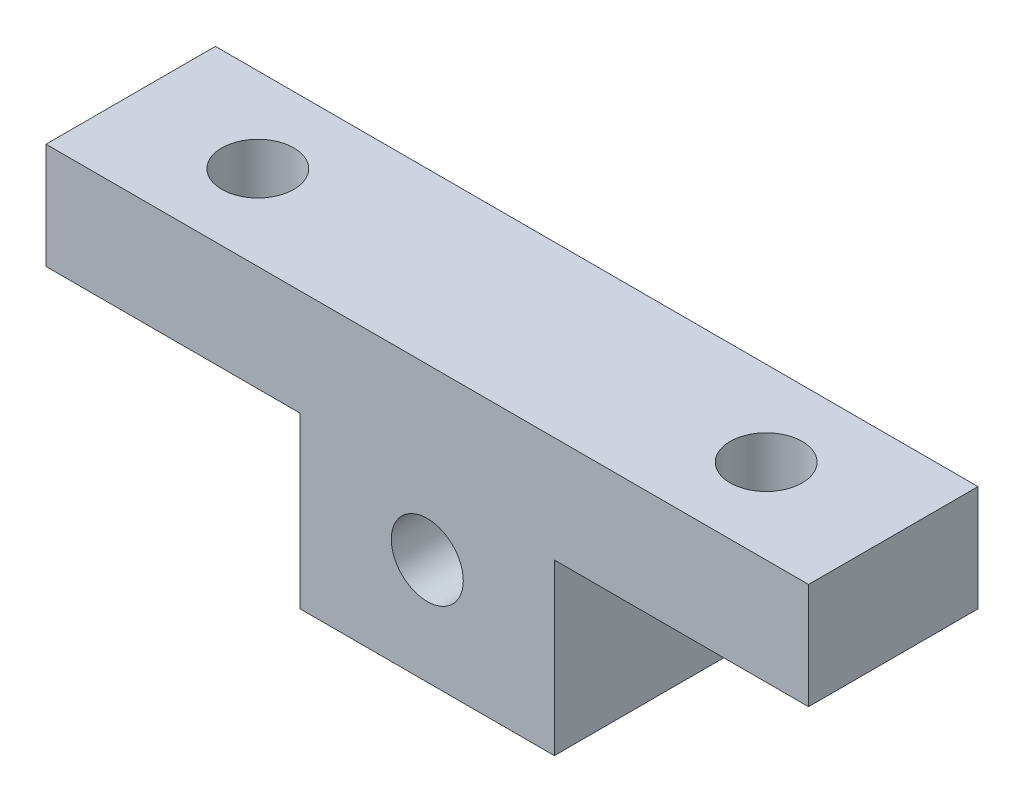
SolidWorks part; units mm, degrees
ref_plane "Front Plane" through (0, 0, 0) normal (0, 0, 1) x (1, 0, 0)
ref_plane "Top Plane" through (0, 0, 0) normal (0, 1, 0) x (1, 0, 0)
ref_plane "Right Plane" through (0, 0, 0) normal (1, 0, 0) x (0, 0, -1)
sketch "Sketch1" plane through (0, 0, 0) normal (0, 0, 1) x (1, 0, 0)
  line L0 (0, 0) -> (0, 5)
  line L1 (0, 5) -> (36, 5)
  line L2 (36, 5) -> (36, 0)
  line L3 (36, 0) -> (24, 0)
  line L4 (24, 0) -> (24, -8)
  line L5 (24, -8) -> (12, -8)
  line L6 (12, -8) -> (12, 0)
  line L7 (12, 0) -> (0, 0)
  dimension "D1" = 36
  dimension "D2" = 12
  dimension "D3" = 12
  dimension "D4" = 12
  dimension "D5" = 5
  dimension "D6" = 8
extrude "Boss-Extrude1" add sketch "Sketch1" along normal blind 8
hole_wizard "M3 Clearance Hole1" positions "Sketch2" profile "Sketch3" hole size "M3" standard "ANSI Metric" end condition through all
sketch "Sketch2" plane through (0, 0, 8) normal (0, 0, 1) x (1, 0, 0)
  line L1 (12, 0) -> (12, -8) construction
  line L2 (36, 5) -> (0, 5) construction
  point P0 (18, -3)
  dimension "D1" = 8
  dimension "D2" = 6
sketch "Sketch3" plane through (18, -3, 8) normal (1, 0, 0) x (0, -1, 0)
  line L0 (0, 0) -> (0, 8)
  line L1 (0, 8) -> (1.7, 8)
  line L2 (1.7, 8) -> (1.7, 0)
  line L5 (1.7, 0) -> (0, 0)
  line L11 (0, -6.35) -> (0, 107.95) construction
  dimension "Thru Hole Dia." = 3.4
  dimension "Thru Hole Depth" = 8
hole_wizard "M3 Clearance Hole2" positions "Sketch4" profile "Sketch5" hole size "M3" standard "ANSI Metric" end condition through all
sketch "Sketch4" plane through (0, 0, 0) normal (0, -1, 0) x (-1, 0, 0)
  line L0 (0, -8) -> (0, 0) construction
  line L1 (-36, -8) -> (-36, 0) construction
  line L2 (-6, -4) -> (-30, -4) construction
  line L4 (-12, 0) -> (-24, 0) construction
  point P0 (-6, -4)
  point P2 (-30, -4)
  dimension "D1" = 6
  dimension "D2" = 6
  dimension "D3" = 4
sketch "Sketch5" plane through (6, 0, 4) normal (1, 0, 0) x (0, 0, -1)
  line L0 (0, 0) -> (0, 5)
  line L1 (0, 5) -> (1.7, 5)
  line L2 (1.7, 5) -> (1.7, 0)
  line L5 (1.7, 0) -> (0, 0)
  line L11 (0, -6.35) -> (0, 107.95) construction
  dimension "Thru Hole Dia." = 3.4
  dimension "Thru Hole Depth" = 5
equation "\"D2@Sketch1\"=\"D1@Sketch1\"/3"
equation "\"D3@Sketch1\"=\"D2@Sketch1\""
